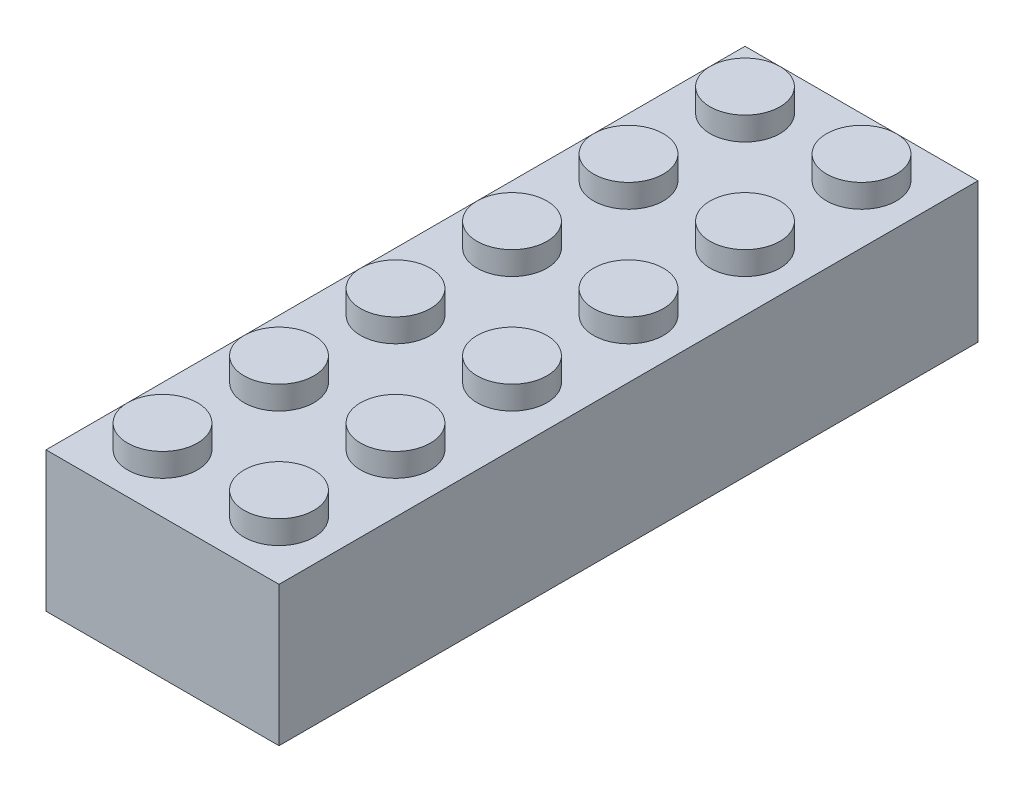
SolidWorks part; units mm, degrees
ref_plane "Front Plane" through (0, 0, 0) normal (0, 0, 1) x (1, 0, 0)
ref_plane "Top Plane" through (0, 0, 0) normal (0, 1, 0) x (1, 0, 0)
ref_plane "Right Plane" through (0, 0, 0) normal (1, 0, 0) x (0, 0, -1)
sketch "Sketch1" plane through (0, 0, 0) normal (0, 1, 0) x (1, 0, 0)
  line L1 (0, 0) -> (16, 0)
  line L2 (0, 0) -> (0, 48)
  line L3 (0, 48) -> (16, 48)
  line L4 (16, 0) -> (16, 48)
  dimension "D1" = 16
  dimension "D2" = 48
extrude "Boss-Extrude1" add sketch "Sketch1" along normal blind 9.6
sketch "Sketch2" plane through (0, 9.6, 0) normal (0, 1, 0) x (1, 0, 0)
  line L0 (8, 0) -> (8, 48) construction
  line L1 (0, 0) -> (16, 0) construction
  line L2 (16, 48) -> (0, 48) construction
  line L3 (16, 0) -> (16, 4) construction
  line L4 (16, 0) -> (16, 48) construction
  line L5 (16, 4) -> (12, 4) construction
  circle A0 centre (12, 4) radius 2.4
  dimension "D3" = 4.8
  dimension "D1" = 4
  dimension "D2" = 4
extrude "Boss-Extrude2" add sketch "Sketch2" along normal blind 1.6
pattern_linear "LPattern1" count 2 spacing 8 along (-1, 0, 0) count 6 spacing 8 along (0, 0, -1) of "Boss-Extrude2"
shell "Shell1" thickness 1.6
